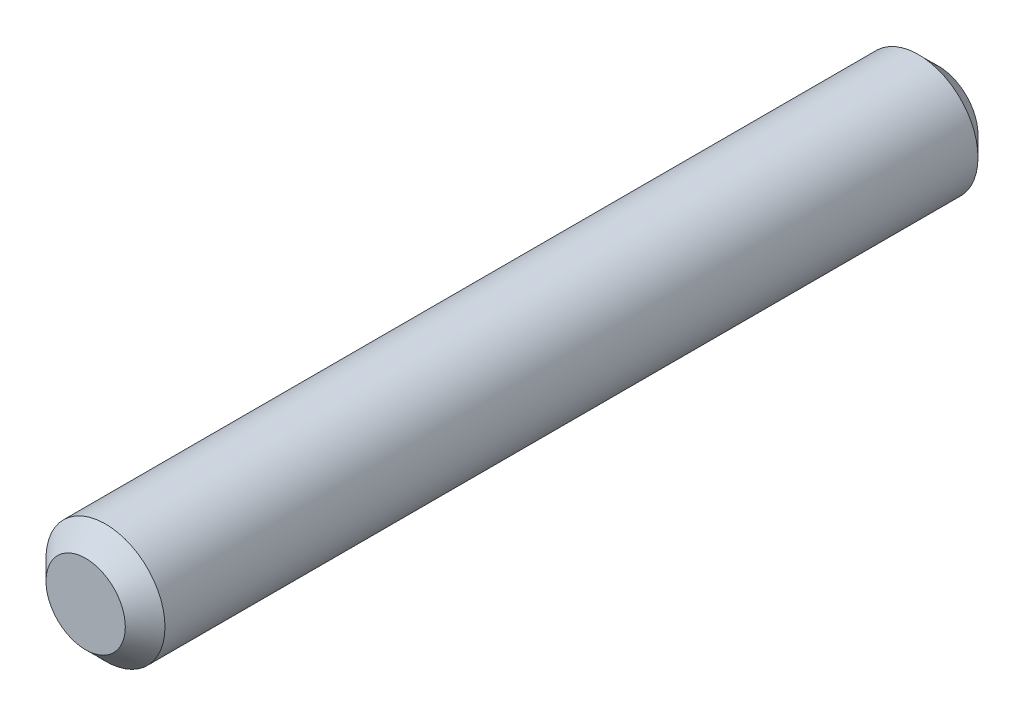
SolidWorks part; units mm, degrees
material "AISI 4140 Steel, quenched & tempered"
ref_plane "Front Plane" through (0, 0, 0) normal (1, 0, 0) x (0, 1, 0)
ref_plane "Top Plane" through (0, 0, 0) normal (0, 0, 1) x (0, 1, 0)
ref_plane "Right Plane" through (0, 0, 0) normal (0, 1, 0) x (-1, 0, 0)
sketch "Sketch1" plane through (0, 0, 0) normal (0, 0, 1) x (0, 1, 0)
  circle A0 centre (0, 0) radius 3
  dimension "D1" = 6
extrude "Boss-Extrude1" add sketch "Sketch1" along normal blind 43
chamfer "Chamfer1" distance 1 angle 45 2 edges at (3, 0, 0) (3, 0, 43)
